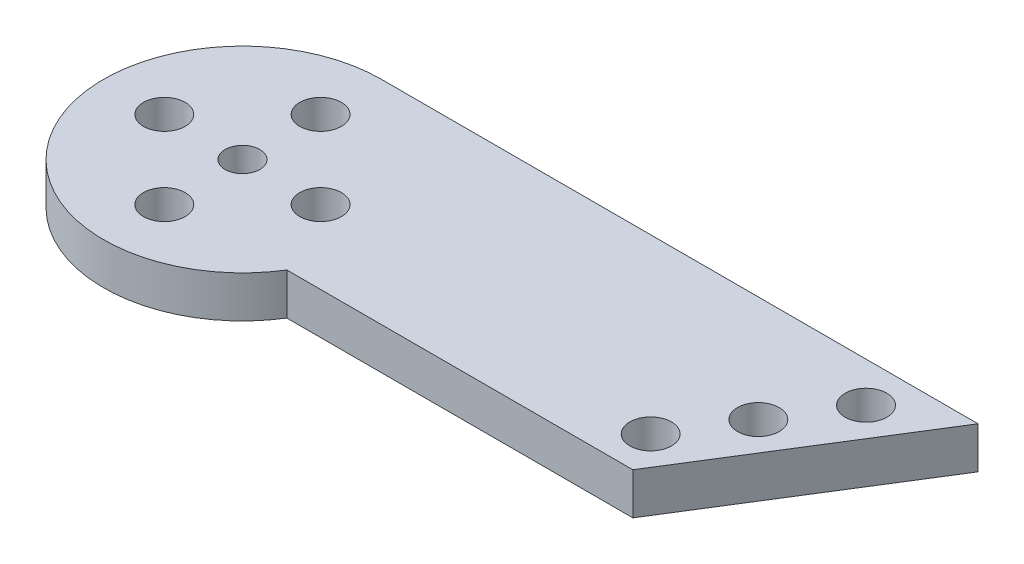
SolidWorks part; units mm, degrees
ref_plane "Front Plane" through (0, 0, 0) normal (0, 0, 1) x (1, 0, 0)
ref_plane "Top Plane" through (0, 0, 0) normal (0, 1, 0) x (1, 0, 0)
ref_plane "Right Plane" through (0, 0, 0) normal (1, 0, 0) x (0, 0, -1)
sketch "Sketch1" plane through (0, 0, 0) normal (0, 1, 0) x (1, 0, 0)
  line L0 (-12.181, 8) -> (22.179, 8)
  line L1 (22.179, 8) -> (12.181, -8)
  line L2 (12.181, -8) -> (-12.181, -8)
  line L3 (13.2604, -1.9324) -> (18.0296, 5.7) construction
  line L4 (12.181, -8) -> (-12.181, 8) construction
  line L5 (0, 0) -> (22.179, 8) construction
  arc A0 (-12.181, 8) -> (-12.181, -8) centre (-12.181, 0) ccw
  circle A1 centre (-12.181, 0) radius 4.5 construction
  circle A2 centre (-12.181, 4.5) radius 1.2
  circle A3 centre (-7.681, 0) radius 1.2
  circle A4 centre (-12.181, -4.5) radius 1.2
  circle A5 centre (-16.681, 0) radius 1.2
  circle A6 centre (18.0296, 5.7) radius 1.2
  circle A7 centre (13.2604, -1.9324) radius 1.2
  circle A8 centre (15.645, 1.8838) radius 1.2
  circle A9 centre (-12.181, 0) radius 1
  dimension "D1" = 16
  dimension "D2" = 9
  dimension "D3" = 2.4
  dimension "D7" = 2.4
  dimension "D10" = 2
  dimension "D4" = 34.36
  dimension "D5" = 58
  dimension "D6" = 9
  dimension "D8" = 2.3
  dimension "D9" = 2.3
extrude "Boss-Extrude1" add sketch "Sketch1" along normal blind 2.4
sketch "Sketch2" plane through (0, 2.4, 0) normal (0, 1, 0) x (1, 0, 0)
  line L0 (14.5353, -4.2324) -> (-5.3923, -4.2324)
  line L1 (12.181, -8) -> (22.179, 8) construction
  line L3 (-12.181, -8) -> (12.181, -8) construction
  line L4 (-12.181, -8) -> (12.181, -8)
  line L5 (12.181, -8) -> (14.5353, -4.2324)
  circle A0 centre (13.2604, -1.9324) radius 1.2 construction
  arc A2 (-12.181, -8) -> (-5.3923, -4.2324) centre (-12.181, 0) ccw
  dimension "D1" = 2.3
extrude "Cut-Extrude1" cut sketch "Sketch2" against normal through all contours L0 A2 L4 L5
